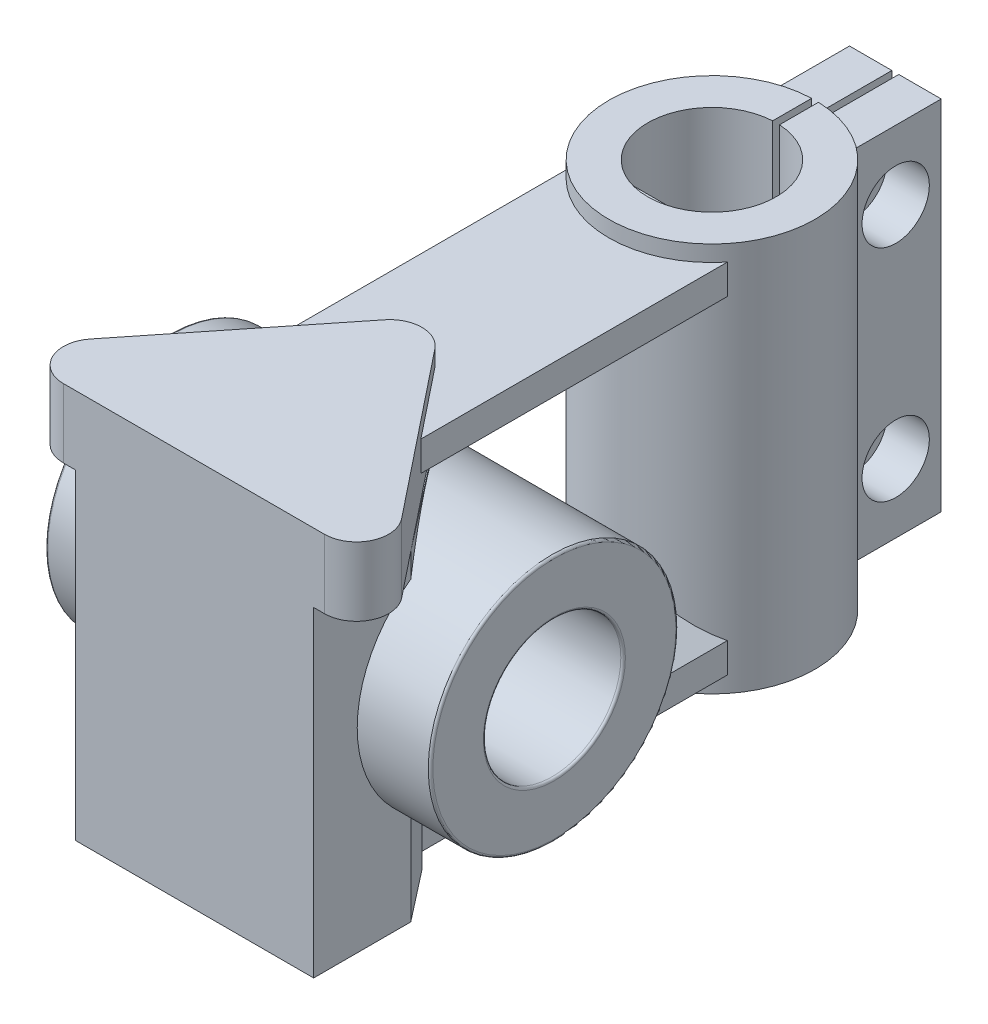
SolidWorks part; units mm, degrees
ref_plane "前视基准面" through (0, 0, 0) normal (0, 0, 1) x (1, 0, 0)
ref_plane "上视基准面" through (0, 0, 0) normal (0, 1, 0) x (1, 0, 0)
ref_plane "右视基准面" through (0, 0, 0) normal (1, 0, 0) x (0, 0, -1)
sketch "草图1" plane through (0, 0, 0) normal (0, 1, 0) x (1, 0, 0)
  line L0 (0, 0) -> (0, 61.6077) construction
  line L3 (-10, 20.1556) -> (-10, 40)
  line L4 (-10, 40) -> (10, 40)
  line L5 (10, 20.1556) -> (10, 40)
  arc A0 (-10, 20.1556) -> (10, 20.1556) centre (0, 0) ccw
  dimension "D1" = 45
  dimension "D2" = 20
  dimension "D4" = 40
extrude "拉伸1" add sketch "草图1" along normal blind 78
sketch "草图3" plane through (0, 78, 0) normal (0, 1, 0) x (1, 0, 0)
  circle A0 centre (0, 0) radius 22.5
extrude "拉伸2" add sketch "草图3" along normal blind 3.5
sketch "草图4" plane through (0, 0, 0) normal (0, -1, 0) x (1, 0, 0)
  circle A0 centre (0, 0) radius 22.5
extrude "拉伸3" add sketch "草图4" along normal blind 3.5
sketch "草图5" plane through (0, 81.5, 0) normal (0, 1, 0) x (1, 0, 0)
  line L0 (0, 40) -> (0, 1.2609) construction
  line L1 (10, 40) -> (-10, 40) construction
  line L3 (-0.75, 41.527) -> (0.75, 41.527)
  line L4 (-0.75, 41.527) -> (-0.75, 4.7623)
  line L5 (-0.75, 4.7623) -> (0.75, 4.7623)
  line L6 (0.75, 41.527) -> (0.75, 4.7623)
  dimension "D1" = 0.75
  dimension "D2" = 1.5
extrude "切除-拉伸1" cut sketch "草图5" against normal through all
sketch "草图6" plane through (0, 81.5, 0) normal (0, 1, 0) x (1, 0, 0)
  circle A0 centre (0, 0) radius 14
  dimension "D1" = 28
extrude "切除-拉伸2" cut sketch "草图6" against normal through all
sketch3d "3D草图1" plane through (0, 0, 0) normal (0, 0, 1) x (1, 0, 0)
sketch3d "3D草图2" plane through (0, 0, 0) normal (0, 0, 1) x (1, 0, 0)
  dimension "D1" = 10
sketch "草图7" plane through (0, 0, 10) normal (0, 0, 1) x (1, 0, 0)
  line L0 (-17.5, 78) -> (17.5, 78)
  line L1 (0, 81.5) -> (0, -31.1013) construction
  line L3 (-17.5, 78) -> (-17.5, 71.5)
  line L4 (-17.5, 71.5) -> (0, 58)
  line L5 (-17.5, 6.5) -> (0, 20)
  line L7 (22.5, 39) -> (55.666, 39) construction
  line L10 (17.5, 78) -> (17.5, 71.5)
  line L12 (17.5, 71.5) -> (0, 58)
  line L13 (0, -3.5) -> (0, 109.1013) construction
  line L18 (17.5, 0) -> (17.5, 6.5)
  line L19 (-17.5, 0) -> (-17.5, 6.5)
  line L20 (0, 20) -> (17.5, 6.5)
  line L22 (-17.5, 0) -> (17.5, 0)
  dimension "D3" = 20
  dimension "D4" = 6.5
extrude "拉伸4" add sketch "草图7" along normal blind 71
sketch "草图8" plane through (0, 81.5, 0) normal (0, 1, 0) x (1, 0, 0)
  line L0 (0, -81) -> (0, -45.5481) construction
  line L1 (17.5, -81) -> (-17.5, -81) construction
  line L2 (-43, -113) -> (43, -113)
  line L3 (43, -113) -> (17.5, -81)
  line L4 (17.5, -81) -> (0, -59.0392)
  line L5 (-43, -113) -> (-17.5, -81)
  line L6 (-17.5, -81) -> (0, -59.0392)
  line L7 (10, 40) -> (0.75, 40) construction
  dimension "D1" = 86
  dimension "D2" = 153
extrude "拉伸5" add sketch "草图8" against normal blind 15
fillet "圆角1" radius 7 3 edges at (0, 79.75, 59.0392) (-43, 74, 113) (43, 74, 113)
sketch "草图9" plane through (0, 66.5, 0) normal (0, -1, 0) x (1, 0, 0)
  line L0 (-28.4711, 113) -> (28.4711, 113) construction
  line L1 (-25.881, 113) -> (26.119, 113)
  line L2 (-25.881, 113) -> (-25.881, 91.5174)
  line L4 (26.119, 113) -> (26.119, 91.816)
  line L5 (0, 0) -> (0, 93.0344) construction
  line L6 (-25.881, 91.5174) -> (0, 58.3267)
  line L7 (-11.0185, 72.8664) -> (-33.9456, 101.6376) construction
  line L8 (0, 58.3267) -> (26.119, 91.816)
  line L9 (33.9456, 101.6376) -> (11.0185, 72.8664) construction
  dimension "D1" = 52
extrude "拉伸6" add sketch "草图9" along normal up to vertex (70 mm away)
sketch "草图10" plane through (0, -3.5, 0) normal (0, -1, 0) x (1, 0, 0)
  line L0 (17.5, 80.7649) -> (17.5, 14.1421) construction
  line L1 (-17.5, 81) -> (17.5, 81)
  line L2 (-17.5, 81) -> (-17.5, 57.1292)
  line L3 (-17.5, 57.1292) -> (17.5, 57.1292)
  line L4 (17.5, 81) -> (17.5, 57.1292)
extrude "切除-拉伸3" cut sketch "草图10" against normal up to vertex (3.5 mm away) up to point (17.5, 0, 14.1421)
sketch "草图11" plane through (26.119, 0, 0) normal (1, 0, 0) x (0, 0, -1)
  line L0 (40, 39) -> (-125.8236, 39) construction
  line L1 (40, 78) -> (40, 0) construction
  line L2 (-103.5, 39) -> (-103.5, 71.013) construction
  line L3 (-113, -3.5) -> (-113, 66.5) construction
  circle A0 centre (-76.5, 39) radius 27
  dimension "D1" = 54
  dimension "D2" = 9.5
extrude "拉伸7" add sketch "草图11" along normal blind 16
sketch "草图12" plane through (-25.881, 0, 0) normal (-1, 0, 0) x (0, 0, 1)
  circle A0 centre (76.5, 39) radius 27
extrude "拉伸8" add sketch "草图12" along normal blind 16
sketch "草图13" plane through (26.119, 0, 0) normal (-1, 0, 0) x (0, 0, 1)
  circle A0 centre (76.5, 39) radius 27
extrude "拉伸9" add sketch "草图13" along normal up to vertex (68 mm away)
sketch "草图16" plane through (42.119, 0, 0) normal (1, 0, 0) x (0, 0, -1)
  circle A0 centre (-76.5, 39) radius 15
  dimension "D1" = 30
extrude "切除-拉伸4" cut sketch "草图16" against normal through all
fillet "圆角2" radius 0.5 4 edges at (-41.881, 39, 103.5) (-41.881, 39, 61.5) (42.119, 39, 61.5) (42.119, 39, 49.5)
hole_wizard "5/8-18 螺纹孔1" positions "草图18" profile "草图20" tap size "5/8-18" standard "Ansi Inch"
sketch "草图18" plane through (10, 0, 0) normal (1, 0, 0) x (0, 0, -1)
  line L0 (30.0778, 78) -> (30.0778, -3.2209) construction
  line L1 (20.1556, 78) -> (40, 78) construction
  line L2 (20.1556, 0) -> (40, 0) construction
  point P0 (30.0778, 63)
  point P6 (30.0778, 15)
  dimension "D1" = 15
  dimension "D2" = 15
sketch "草图20" plane through (10, 63, -30.0778) normal (0, 1, 0) x (0, 0, -1)
  line L0 (0, 0) -> (0, 43.2099)
  line L1 (0, 43.2099) -> (7.3419, 38.7985)
  line L2 (7.3419, 38.7985) -> (7.3419, 0)
  line L5 (7.3419, 0) -> (0, 0)
  line L10 (0, 43.2099) -> (-7.3419, 38.7985) construction
  line L11 (0, -6.35) -> (0, 107.95) construction
  dimension "蹟恇謂郰芛眻噤" = 14.6837
  dimension "蹟恇謂郰芛旮僅" = 38.7985
  dimension "絳芛褒僅" = 118
cosmetic thread "孔螺蚊线1" parameters "D1"=31.75, "D2"=15.875
cosmetic thread "孔螺蚊线2" parameters "D1"=31.75, "D2"=15.875
